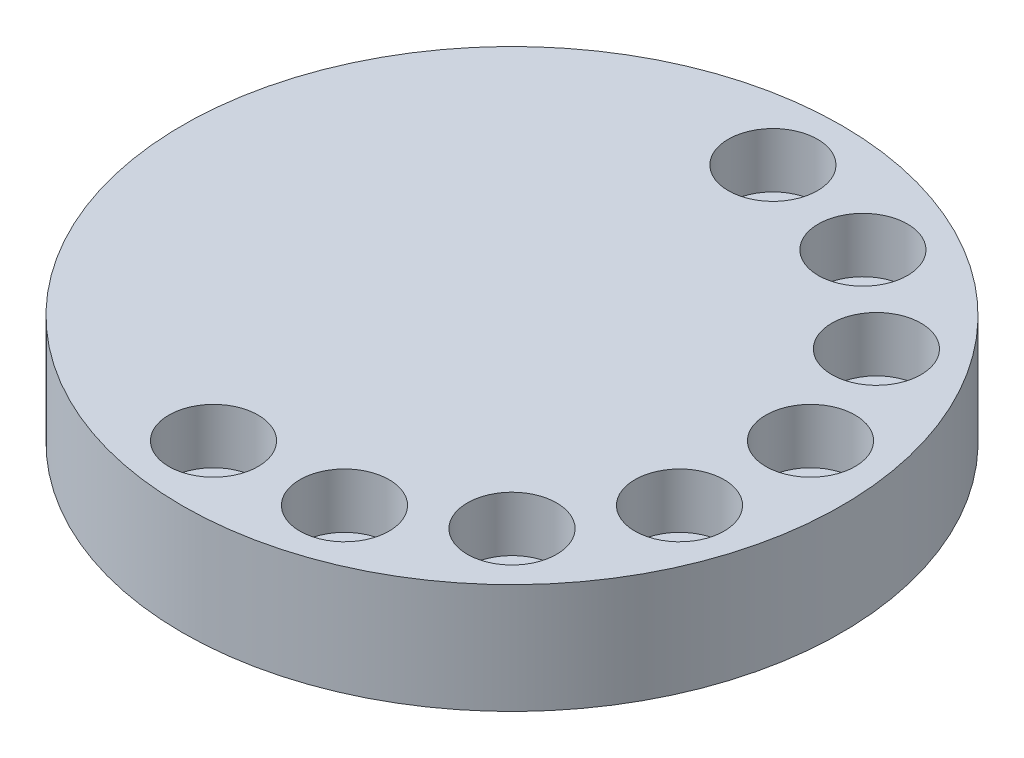
SolidWorks part; units mm, degrees
ref_plane "Front Plane" through (0, 0, 0) normal (0, 0, 1) x (1, 0, 0)
ref_plane "Top Plane" through (0, 0, 0) normal (0, 1, 0) x (1, 0, 0)
ref_plane "Right Plane" through (0, 0, 0) normal (1, 0, 0) x (0, 0, -1)
sketch "Sketch1" plane through (0, 0, 0) normal (0, 1, 0) x (1, 0, 0)
  circle A0 centre (0, 0) radius 76.2
  dimension "D1" = 152.4
extrude "Boss-Extrude1" add sketch "Sketch1" along normal blind 25.4
hole_wizard "CBORE for 1/2 Socket Head Cap Screw1" positions "Sketch3" profile "Sketch2" counterbore size "1/2" standard "ANSI Inch" end condition through all
sketch "Sketch3" plane through (0, 25.4, 0) normal (0, 1, 0) x (1, 0, 0)
  line L0 (0, 0) -> (0, 60.325) construction
  point P0 (0, 60.325)
  dimension "D1" = 60.325
sketch "Sketch2" plane through (0, 25.4, -60.325) normal (1, 0, 0) x (0, 0, 1)
  line L0 (0, 0) -> (0, 25.4)
  line L1 (0, 25.4) -> (6.7462, 25.4)
  line L3 (6.7462, 25.4) -> (6.7462, 12.7)
  line L4 (6.7462, 12.7) -> (10.3187, 12.7)
  line L5 (10.3187, 12.7) -> (10.3187, 0)
  line L7 (10.3187, 0) -> (0, 0)
  line L11 (0, -6.35) -> (0, 107.95) construction
  dimension "Thru Hole Dia." = 13.4925
  dimension "Thru Hole Depth" = 25.4
  dimension "C'Bore Dia." = 20.6375
  dimension "C'Bore Depth" = 12.7
pattern_circular "CirPattern1" count 8 every 27 about axis through (0, 0, 0) along (0, 1, 0) of "CBORE for 1/2 Socket Head Cap Screw1"
